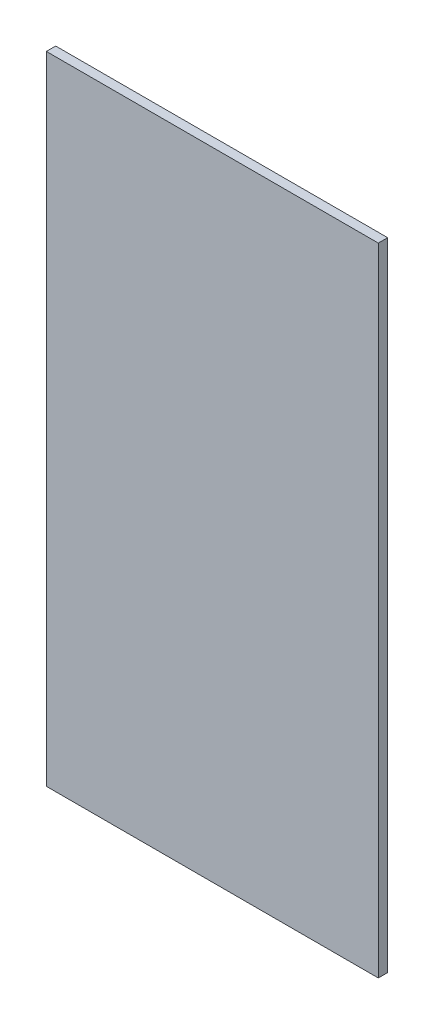
SolidWorks part; units mm, degrees
material "Acrílico (Impacto medio-alto)"
ref_plane "Alzado" through (0, 0, 0) normal (0, 0, 1) x (1, 0, 0)
ref_plane "Planta" through (0, 0, 0) normal (0, 1, 0) x (1, 0, 0)
ref_plane "Vista lateral" through (0, 0, 0) normal (1, 0, 0) x (0, 0, -1)
sketch "Croquis1" plane through (0, 0, 0) normal (0, 0, 1) x (1, 0, 0)
  line L1 (177.35, -340) -> (-177.35, -340)
  line L2 (177.35, -340) -> (177.35, 340)
  line L3 (177.35, 340) -> (-177.35, 340)
  line L4 (-177.35, -340) -> (-177.35, 340)
  line L5 (177.35, -340) -> (-177.35, 340) construction
  line L6 (177.35, 340) -> (-177.35, -340) construction
  point P0 (0, 0)
  dimension "D1" = 680
  dimension "D2" = 354.7
extrude "Saliente-Extruir1" add sketch "Croquis1" along normal blind 10
